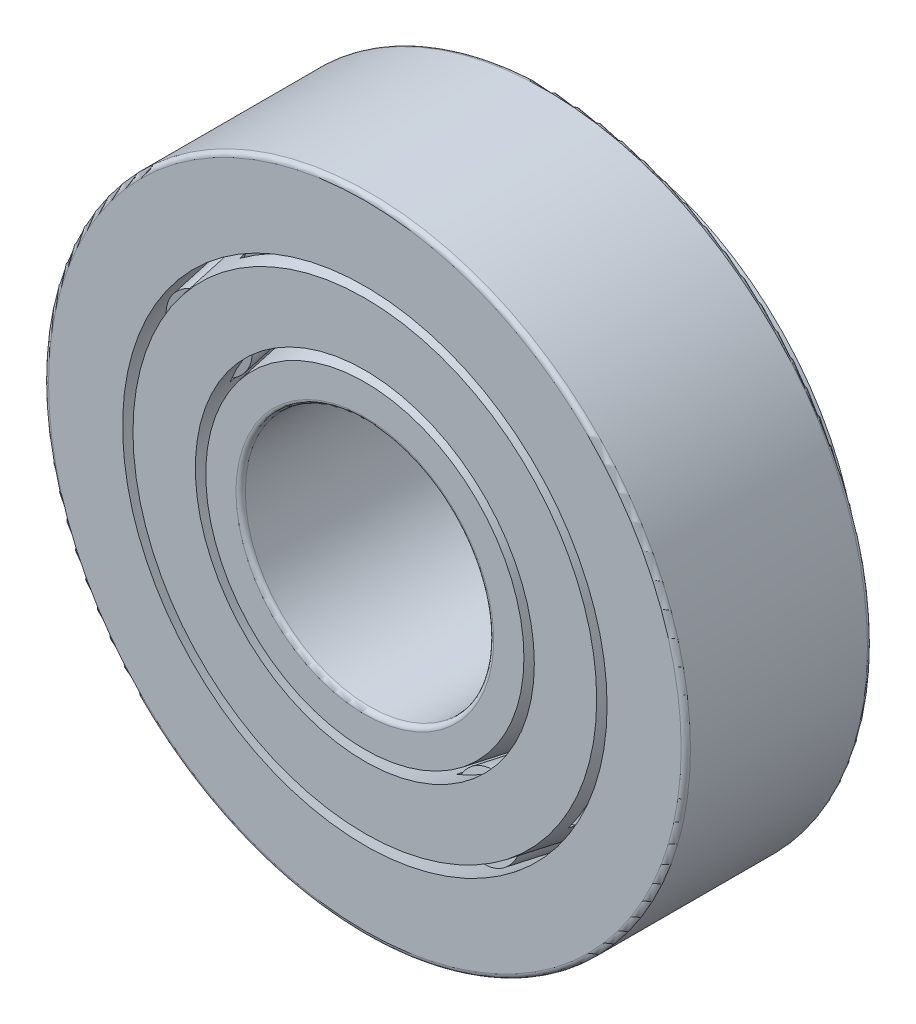
SolidWorks part; units mm, degrees
material "1060 Alloy"
ref_plane "Front Plane" through (0, 0, 0) normal (0, 0, 1) x (1, 0, 0)
ref_plane "Top Plane" through (0, 0, 0) normal (0, 1, 0) x (1, 0, 0)
ref_plane "Right Plane" through (0, 0, 0) normal (1, 0, 0) x (0, 0, -1)
sketch "Sketch1" plane through (0, 0, 0) normal (1, 0, 0) x (0, 0, -1)
  line L0 (-9.525, 0) -> (9.525, 0) construction
  line L1 (0, 0) -> (0, 24.6126) construction
  line L2 (-9.525, 9.525) -> (9.525, 9.525) construction
  line L3 (9.525, 9.525) -> (9.525, 15.56) construction
  line L4 (9.525, 15.56) -> (-9.525, 12.201) construction
  line L5 (-9.525, 12.201) -> (-9.525, 9.525) construction
  line L7 (-9.525, 24.6126) -> (4.7625, 24.6126)
  line L8 (4.7625, 24.6126) -> (4.7625, 21.0968)
  line L9 (4.7625, 21.0968) -> (-9.525, 18.5776)
  line L10 (-9.525, 18.5776) -> (-9.525, 24.6126)
  line L11 (-9.525, 18.5776) -> (-8.4345, 12.3933) construction
  line L12 (7.4185, 21.5652) -> (8.509, 15.3809) construction
  line L14 (-9.525, 12.201) -> (-8.4345, 12.3933) construction
  line L15 (-9.525, 12.201) -> (8.509, 15.3809) construction
  point P5 (0, 9.525)
  dimension "D1" = 100
  dimension "Width" = 19.05
  dimension "OD" = 49.2252
  dimension "Shaft Dia" = 19.05
  dimension "D2" = 15.0876
  dimension "D3" = 6.035
  dimension "Outer Wd" = 14.2875
  dimension "Bearing Wd" = 18.034
revolve "Revolve1" add sketch "Sketch1" angle 360 about L0
sketch "Sketch5" plane through (0, 0, 0) normal (1, 0, 0) x (0, 0, -1)
  line L0 (9.525, 15.56) -> (-9.525, 12.201) construction
  line L1 (9.525, 15.56) -> (-9.525, 12.201)
  line L2 (-9.525, 12.201) -> (-9.525, 9.525)
  line L3 (-9.525, 9.525) -> (9.525, 9.525)
  line L4 (9.525, 9.525) -> (9.525, 15.56)
revolve "Revolve4" add sketch "Sketch5" angle 360 about L0
sketch "Sketch2" plane through (0, 0, 0) normal (1, 0, 0) x (0, 0, -1)
  line L0 (-9.525, 17.7805) -> (-9.525, 12.9981)
  line L1 (4.7625, 20.2998) -> (7.5549, 20.7921)
  line L2 (-9.525, 12.9981) -> (4.7625, 15.5174)
  line L3 (7.4185, 21.5652) -> (8.509, 15.3809) construction
  line L4 (4.7625, 15.5174) -> (4.7625, 20.2998) construction
  line L5 (4.7625, 20.2998) -> (-9.525, 17.7805)
  line L6 (4.7625, 21.0968) -> (-9.525, 18.5776) construction
  line L7 (9.525, 15.56) -> (-9.525, 12.201) construction
  line L8 (-9.525, 18.5776) -> (4.7625, 21.0968) construction
  line L9 (-9.525, 12.201) -> (8.509, 15.3809) construction
  line L10 (7.5549, 20.7921) -> (8.3727, 16.1539)
  line L11 (-9.525, 18.5776) -> (-9.525, 17.7805) construction
  line L12 (-9.525, 12.9981) -> (-9.525, 12.201) construction
  line L13 (4.7625, 24.6126) -> (4.7625, 21.0968) construction
  line L14 (8.3727, 16.1539) -> (4.7625, 15.5174)
  dimension "D1" = 6.2797
  dimension "D2" = 4.7098
revolve "Revolve2" add sketch "Sketch2" angle 360 about L0
sketch "Sketch3" plane through (0, 0, 0) normal (1, 0, 0) x (0, 0, -1)
  line L0 (-9.525, 15.3893) -> (4.7625, 17.9086) construction
  line L1 (-9.525, 17.7805) -> (-9.525, 12.9981) construction
  line L2 (4.7625, 15.5174) -> (4.7625, 20.2998) construction
  line L3 (-7.8893, 15.6777) -> (-8.4345, 18.7698)
  line L5 (-8.4345, 18.7698) -> (4.2173, 21.0007)
  line L6 (4.2173, 21.0007) -> (4.7625, 17.9086)
  line L7 (4.7625, 17.9086) -> (-7.8893, 15.6777)
  line L8 (4.7625, 21.0968) -> (-9.525, 18.5776) construction
  line L9 (-9.525, 15.3893) -> (-8.9798, 15.4854) construction
  line L10 (-9.525, 18.5776) -> (-8.4345, 12.3933) construction
  line L11 (-8.9798, 15.4854) -> (-8.4345, 15.5816) construction
  line L12 (-8.4345, 15.5816) -> (-7.8893, 15.6777) construction
revolve "Cut-Revolve1" cut sketch "Sketch3" angle 360 about L0
sketch "Sketch4" plane through (0, 0, 0) normal (1, 0, 0) x (0, 0, -1)
  line L0 (-8.3904, 18.5197) -> (4.2614, 20.7506)
  line L1 (4.2614, 20.7506) -> (4.7625, 17.9086)
  line L2 (4.7625, 17.9086) -> (-7.8893, 15.6777)
  line L3 (-9.525, 15.3893) -> (-7.8893, 15.6777) construction
  line L4 (-7.8893, 15.6777) -> (-8.3904, 18.5197)
  line L6 (4.7625, 17.9086) -> (-7.8893, 15.6777) construction
  line L7 (4.7625, 21.0968) -> (-9.525, 18.5776) construction
  dimension "D1" = 0.254
revolve "Revolve3" add sketch "Sketch4" angle 360 about L0
ref_axis "Axis1" through (0, 0, -9.525) along (0, 0, 1)
pattern_circular "CirPattern1" count 12 every 30 about axis through (0, 0, 0) along (0, 0, 1) of "Cut-Revolve1"
pattern_circular "CirPattern2" count 12 every 30 about axis through (0, 0, -9.525) along (0, 0, 1) of bodies 403
fillet "Fillet1" radius 0.3572 2 edges at (24.6126, 0, -4.7625) (24.6126, 0, 9.525)
fillet "Fillet2" radius 0.3572 2 edges at (9.525, 0, -9.525) (9.525, 0, 9.525)
sketch "Sketch6" plane through (0, 0, 0) normal (1, 0, 0) x (0, 0, -1)
  line L0 (-49.2125, 24.6126) -> (-49.2125, 18.5776)
  line L1 (-49.2125, 18.5776) -> (-34.925, 21.0968)
  line L2 (-34.925, 21.0968) -> (-34.925, 24.6126)
  line L3 (-34.925, 24.6126) -> (-49.2125, 24.6126)
  line L4 (-9.525, 24.6126) -> (4.7625, 24.6126) construction
  line L5 (-9.525, 18.5776) -> (-9.525, 24.6126) construction
  line L6 (4.7625, 24.6126) -> (4.7625, 21.0968) construction
  line L8 (-9.525, 24.2554) -> (-9.525, -24.2554) construction
  dimension "D1" = 25.4
revolve "Revolve5" [suppressed] add sketch "Sketch6" angle 360 about L0
fillet "Fillet3" [suppressed] radius 0.3572
delete or keep bodies "Body-Delete1" [suppressed] type delete bodies bodies 399
equation "\"D3@Sketch1\" = \"D2@Sketch1\"/2.5"
equation "\"D2@Sketch2\" = \"D1@Sketch2\"*.75"
equation "\"Rollers@CirPattern2\" = \"OD@Sketch1\"*6"
equation "\"Angle@CirPattern2\" = 360/\"Rollers@CirPattern2\""
equation "\"D1@CirPattern1\" = \"Rollers@CirPattern2\""
equation "\"D2@CirPattern1\" = \"Angle@CirPattern2\""
equation "\"D1@Fillet1\" = \"Outer Wd@Sketch1\"*.025"
equation "\"D1@Fillet2\" = \"D1@Fillet1\""
equation "\"D1@Fillet3\" = \"D1@Fillet1\""
